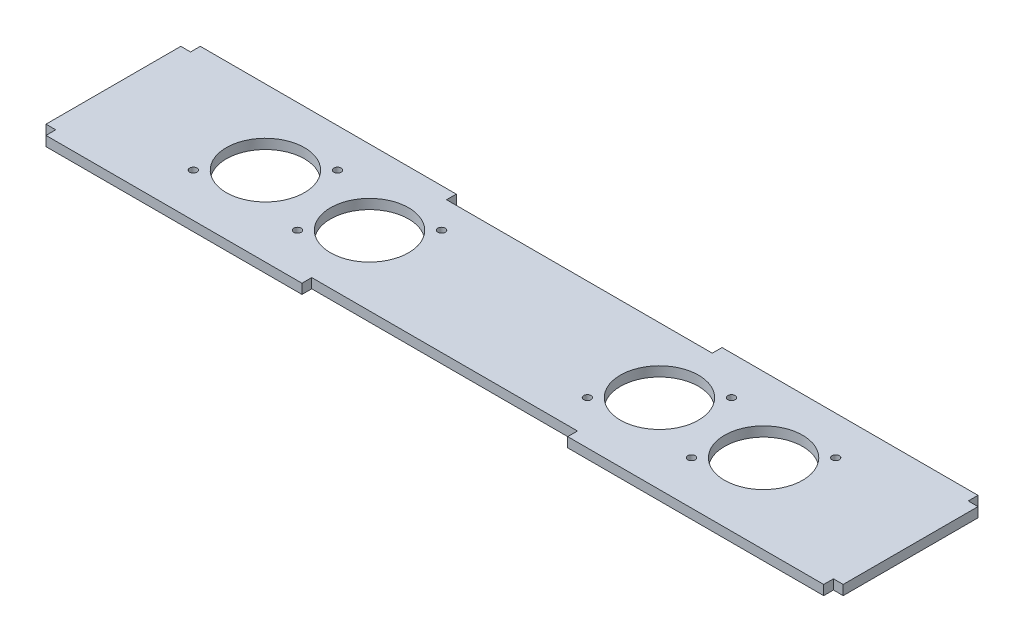
SolidWorks part; units mm, degrees
ref_plane "Front Plane" through (0, 0, 0) normal (0, 0, 1) x (1, 0, 0)
ref_plane "Top Plane" through (0, 0, 0) normal (0, 1, 0) x (1, 0, 0)
ref_plane "Right Plane" through (0, 0, 0) normal (1, 0, 0) x (0, 0, -1)
sketch "Sketch2" plane through (0, 0, 0) normal (0, 1, 0) x (1, 0, 0)
  line L1 (0, 0) -> (490, 0)
  line L2 (0, 0) -> (0, 94.85)
  line L3 (0, 94.85) -> (490, 94.85)
  line L4 (490, 0) -> (490, 94.85)
  dimension "D1" = 94.85
  dimension "D2" = 490
extrude "Boss-Extrude1" add sketch "Sketch2" along normal blind 6
sketch "Sketch4" plane through (0, 6, 0) normal (0, 1, 0) x (1, 0, 0)
  line L1 (490, 0) -> (484, 0)
  line L2 (490, 0) -> (490, 6)
  line L3 (490, 6) -> (484, 6)
  line L4 (484, 0) -> (484, 6)
  line L5 (490, 94.85) -> (484, 94.85)
  line L6 (490, 94.85) -> (490, 88.85)
  line L7 (490, 88.85) -> (484, 88.85)
  line L8 (484, 94.85) -> (484, 88.85)
  line L9 (0, 94.85) -> (6, 94.85)
  line L10 (0, 94.85) -> (0, 88.85)
  line L11 (0, 88.85) -> (6, 88.85)
  line L12 (6, 94.85) -> (6, 88.85)
  line L13 (0, 0) -> (6, 0)
  line L14 (0, 0) -> (0, 6)
  line L15 (0, 6) -> (6, 6)
  line L16 (6, 0) -> (6, 6)
  dimension "D1" = 6
  dimension "D2" = 6
  dimension "D3" = 82.85
extrude "Cut-Extrude2" cut sketch "Sketch4" against normal through all
sketch "Sketch5" plane through (0, 6, 0) normal (0, 1, 0) x (1, 0, 0)
  line L0 (484, 94.85) -> (6, 94.85) construction
  line L1 (163.3333, 94.85) -> (326.6667, 94.85)
  line L2 (163.3333, 94.85) -> (163.3333, 88.85)
  line L3 (163.3333, 88.85) -> (326.6667, 88.85)
  line L4 (326.6667, 94.85) -> (326.6667, 88.85)
  line L5 (0, 88.85) -> (0, 6) construction
  line L6 (6, 0) -> (484, 0) construction
  line L7 (163.3333, 0) -> (326.6667, 0)
  line L8 (163.3333, 0) -> (163.3333, 6)
  line L9 (163.3333, 6) -> (326.6667, 6)
  line L10 (326.6667, 0) -> (326.6667, 6)
  dimension "D1" = 6
  dimension "D2" = 163.3333
  dimension "D3" = 163.3333
  dimension "D4" = 163.3333
extrude "Cut-Extrude3" cut sketch "Sketch5" against normal through all
hole_wizard "M4 Clearance Slot1" positions "Sketch6" profile "Sketch7" size "M4" standard "ANSI Metric" slot yes
sketch "Sketch6" plane through (0, 6, 0) normal (0, 1, 0) x (1, 0, 0)
  point P0 (375.9521, 26.8063)
  point P3 (420.2521, 71.1063)
  point P6 (356.2521, 71.1063)
  point P9 (311.9521, 26.8063)
  point P12 (178.0479, 71.1063)
  point P15 (133.7479, 26.8063)
  point P18 (114.0479, 71.1063)
  point P21 (69.7479, 26.8063)
sketch "Sketch7" plane through (375.9521, 6, -26.8063) normal (1, 0, 0) x (0, 0, 1)
  line L0 (0, 0) -> (0, 19.3519)
  line L1 (0, 19.3519) -> (2.25, 18)
  line L2 (2.25, 18) -> (2.25, 0)
  line L5 (2.25, 0) -> (0, 0)
  line L10 (0, 19.3519) -> (-2.25, 18) construction
  line L11 (0, -6.35) -> (0, 107.95) construction
  dimension "Hole Dia." = 4.5
  dimension "Hole Depth" = 18
  dimension "Drill Angle" = 118
hole_wizard "M45 Clearance Slot1" positions "Sketch8" profile "Sketch9" size "M45" standard "ANSI Metric" slot yes
sketch "Sketch8" plane through (0, 6, 0) normal (0, 1, 0) x (1, 0, 0)
  point P0 (91.8979, 48.9563)
  point P3 (155.8979, 48.9563)
  point P6 (334.1021, 48.9563)
  point P9 (398.1021, 48.9563)
sketch "Sketch9" plane through (91.8979, 6, -48.9563) normal (1, 0, 0) x (0, 0, 1)
  line L0 (0, 0) -> (0, 32.4207)
  line L1 (0, 32.4207) -> (24, 18)
  line L2 (24, 18) -> (24, 0)
  line L5 (24, 0) -> (0, 0)
  line L10 (0, 32.4207) -> (-24, 18) construction
  line L11 (0, -6.35) -> (0, 107.95) construction
  dimension "Hole Dia." = 48
  dimension "Hole Depth" = 18
  dimension "Drill Angle" = 118
